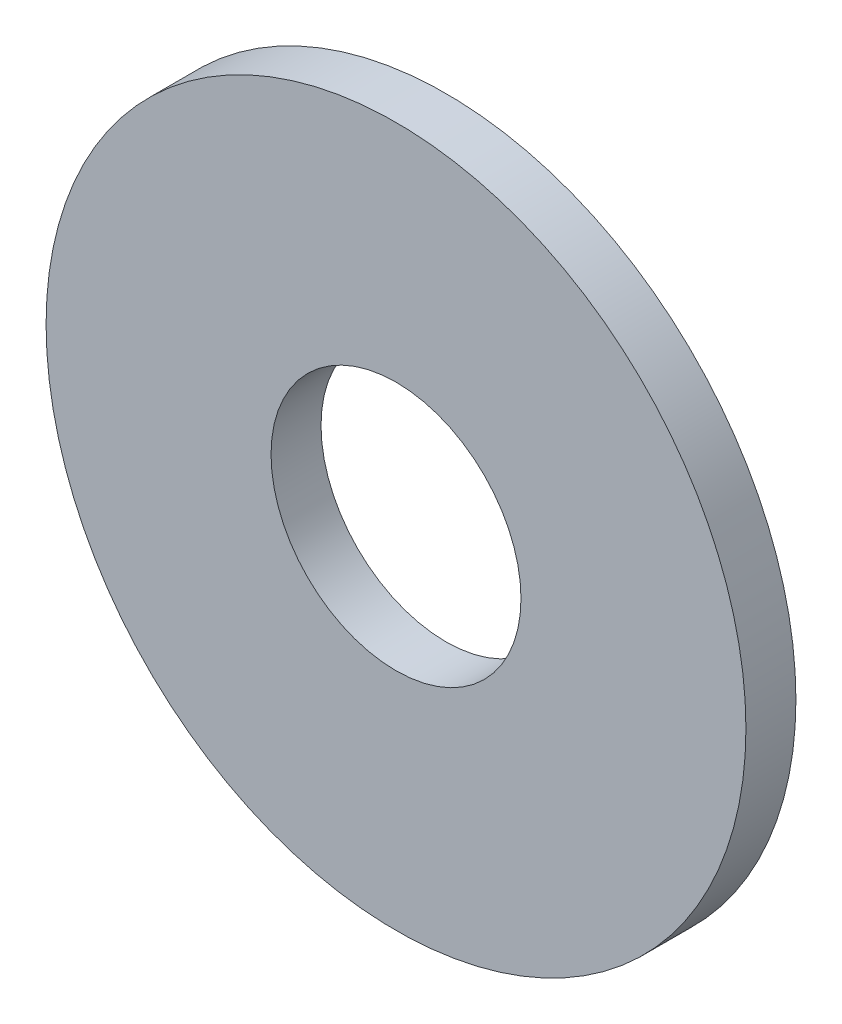
SolidWorks part; units mm, degrees
ref_plane "Plano frontal" through (0, 0, 0) normal (0, 0, 1) x (1, 0, 0)
ref_plane "Plano superior" through (0, 0, 0) normal (0, 1, 0) x (1, 0, 0)
ref_plane "Plano direito" through (0, 0, 0) normal (1, 0, 0) x (0, 0, -1)
sketch "Esboço1" plane through (0, 0, 0) normal (0, 0, 1) x (1, 0, 0)
  circle A0 centre (0, 0) radius 7
  circle A1 centre (0, 0) radius 2.5
  dimension "D1" = 14
  dimension "D2" = 5
extrude "Ressalto-extrusão1" add sketch "Esboço1" along normal blind 1
